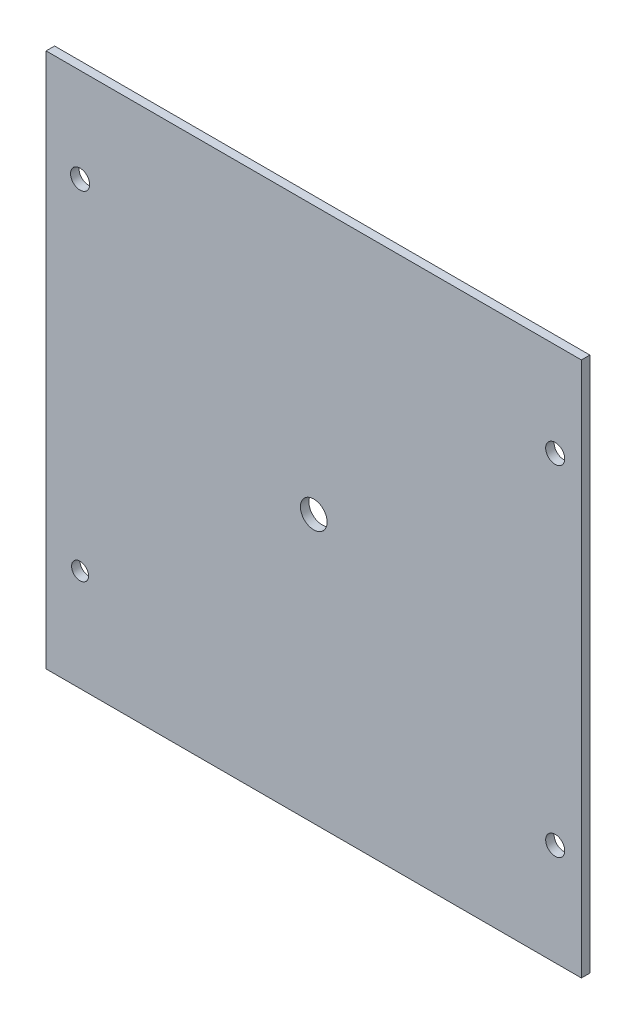
SolidWorks part; units mm, degrees
ref_plane "Front Plane" through (0, 0, 0) normal (0, 0, 1) x (1, 0, 0)
ref_plane "Top Plane" through (0, 0, 0) normal (0, 1, 0) x (1, 0, 0)
ref_plane "Right Plane" through (0, 0, 0) normal (1, 0, 0) x (0, 0, -1)
sketch "Sketch1" plane through (0, 0, 0) normal (0, 0, 1) x (1, 0, 0)
  line L1 (0, 0) -> (200.3, 0)
  line L2 (0, 0) -> (0, 200.3)
  line L3 (0, 200.3) -> (200.3, 200.3)
  line L4 (200.3, 0) -> (200.3, 200.3)
  circle A0 centre (12.7, 38.1) radius 3.175
  circle A1 centre (12.7, 165.1) radius 3.57
  circle A2 centre (190.5, 165.1) radius 3.57
  circle A3 centre (190.5, 38.1) radius 3.57
  circle A4 centre (100.15, 100.15) radius 5
  point P15 (0, 0)
  point P16 (0, 0)
  point P17 (0, 0)
  point P18 (0, 0)
  point P19 (0, 0)
  point P20 (0, 0)
  point P21 (0, 0)
  point P22 (0, 0)
  point P23 (0, 0)
  point P24 (0, 0)
  point P25 (0, 0)
  point P26 (0, 0)
  point P27 (0, 0)
  point P28 (0, 0)
extrude "Boss-Extrude1" add sketch "Sketch1" along normal blind 3.175
